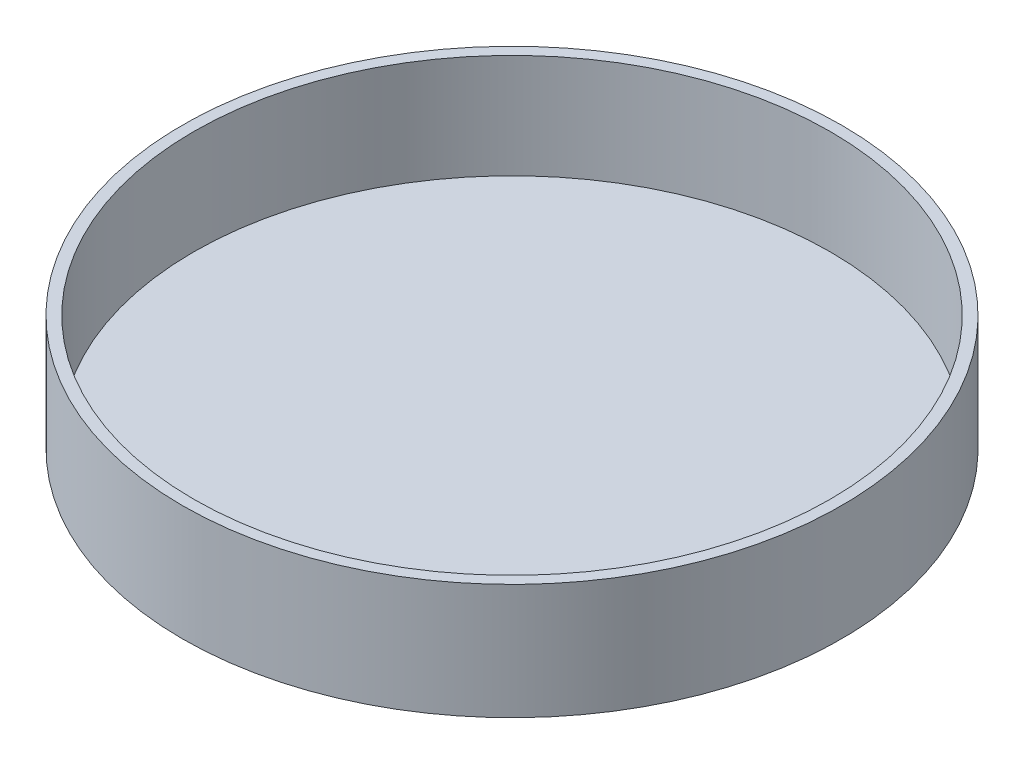
SolidWorks part; units mm, degrees
material "Plexiglas"
ref_plane "Front" through (0, 0, 0) normal (0, 0, 1) x (1, 0, 0)
ref_plane "Top" through (0, 0, 0) normal (0, 1, 0) x (1, 0, 0)
ref_plane "Right" through (0, 0, 0) normal (1, 0, 0) x (0, 0, -1)
sketch "Esquisse1" plane through (0, 0, 0) normal (0, 0, 1) x (1, 0, 0)
  line L0 (0, 0) -> (0, 15.5) construction
  line L1 (0, 0) -> (44.25, 0)
  line L2 (44.25, 15.5) -> (44.25, 0)
  line L3 (44.25, 15.5) -> (42.75, 15.5)
  line L4 (42.75, 15.5) -> (42.75, 1.5)
  line L5 (42.75, 1.5) -> (0, 1.5)
  line L6 (0, 0) -> (0, 1.5)
  dimension "D1" = 15.5
  dimension "D2" = 88.5
  dimension "D3" = 1.5
  dimension "D4" = 1.5
revolve "Révolution1" add sketch "Esquisse1" angle 360 about L0
